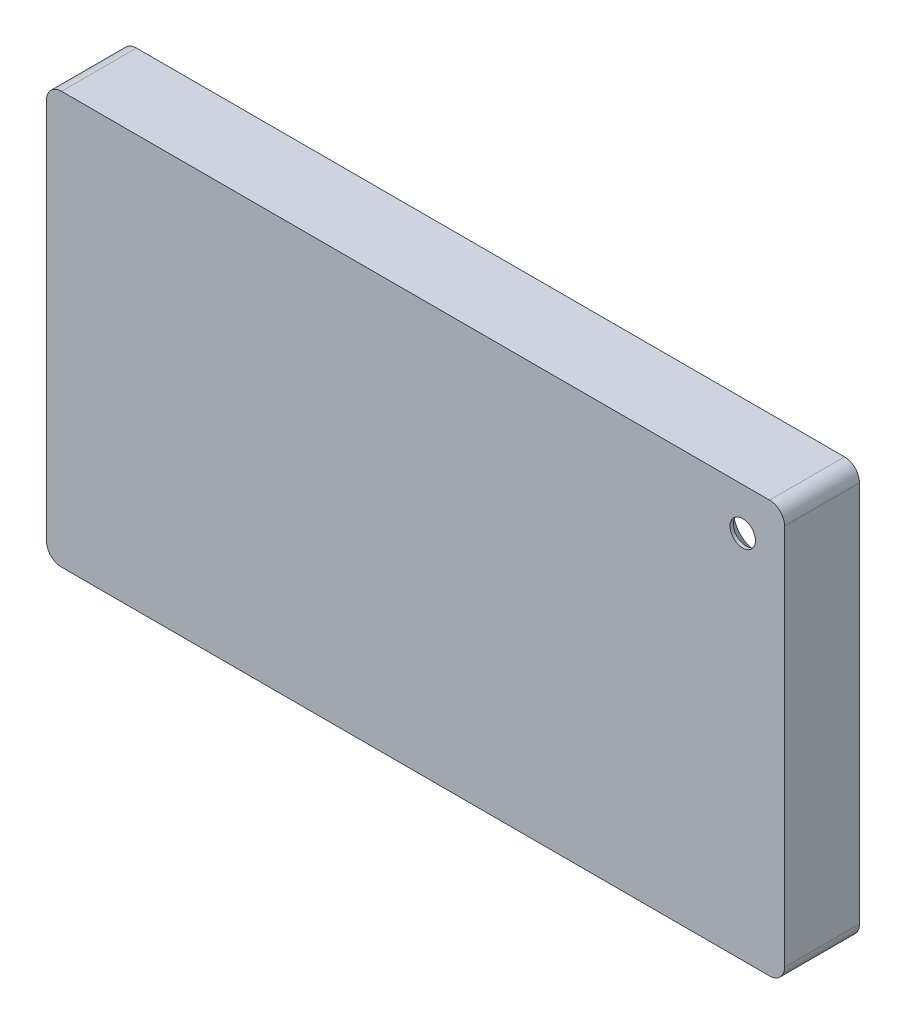
SolidWorks part; units mm, degrees
ref_plane "Front Plane" through (0, 0, 0) normal (0, 0, 1) x (1, 0, 0)
ref_plane "Top Plane" through (0, 0, 0) normal (0, 1, 0) x (1, 0, 0)
ref_plane "Right Plane" through (0, 0, 0) normal (1, 0, 0) x (0, 0, -1)
sketch "Sketch1" plane through (0, 0, 0) normal (0, 0, 1) x (1, 0, 0)
  line L1 (-47.25, -25.5) -> (47.25, -25.5)
  line L2 (-47.25, -25.5) -> (-47.25, 25.5)
  line L3 (-47.25, 25.5) -> (47.25, 25.5)
  line L4 (47.25, -25.5) -> (47.25, 25.5)
  line L5 (-47.25, -25.5) -> (47.25, 25.5) construction
  line L6 (-47.25, 25.5) -> (47.25, -25.5) construction
  point P0 (0, 0)
  dimension "D1" = 51
  dimension "D2" = 94.5
extrude "Boss-Extrude1" add sketch "Sketch1" along normal blind 2
sketch "Sketch2" plane through (0, 0, 2) normal (0, 0, 1) x (1, 0, 0)
  line L0 (-49.25, 27.5) -> (-49.25, -27.5)
  line L1 (-49.25, -27.5) -> (49.25, -27.5)
  line L2 (49.25, -27.5) -> (49.25, 27.5)
  line L3 (49.25, 27.5) -> (-49.25, 27.5)
  line L4 (47.25, -25.5) -> (47.25, 25.5)
  line L5 (47.25, 25.5) -> (-47.25, 25.5)
  line L6 (-47.25, 25.5) -> (-47.25, -25.5)
  line L7 (-47.25, -25.5) -> (47.25, -25.5)
  line L8 (47.25, -25.5) -> (47.25, 25.5)
  line L9 (47.25, 25.5) -> (-47.25, 25.5)
  line L10 (-47.25, 25.5) -> (-47.25, -25.5)
  line L11 (-47.25, -25.5) -> (47.25, -25.5)
  dimension "D1" = 0
  dimension "D2" = 2
extrude "Boss-Extrude2" add sketch "Sketch2" against normal blind 10
sketch "Sketch3" plane through (0, 0, 2) normal (0, 0, 1) x (1, 0, 0)
  circle A0 centre (43.6658, 21.8683) radius 1.7
  dimension "D1" = 3.4
extrude "Cut-Extrude1" cut sketch "Sketch3" against normal through all
chamfer "Chamfer1" distance 1.55 angle 45 1 edges at (41.9658, 21.8683, 0)
ref_plane "Plane1" through (0, 0, -18) normal (0, 0, -1) x (-1, 0, 0)
sketch "Sketch5" plane through (0, 0, -18) normal (0, 0, -1) x (-1, 0, 0)
  circle A0 centre (49.25, -27.5) radius 4
  dimension "D1" = 8
sketch "Sketch6" plane through (0, 0, -8) normal (0, 0, -1) x (-1, 0, 0)
  line L0 (47.25, -25.5) -> (-47.25, -25.5) construction
  line L1 (47.25, -25.5) -> (38.6349, -25.5)
  line L2 (47.25, 25.5) -> (47.25, -25.5) construction
  line L3 (47.25, -19.861) -> (47.25, -25.5)
  line L4 (49.25, 27.5) -> (-49.25, 27.5)
  line L5 (-49.25, 27.5) -> (-49.25, -27.5)
  line L6 (-49.25, -27.5) -> (49.25, -27.5)
  line L7 (49.25, -27.5) -> (49.25, 27.5)
  line L10 (38.6349, -27.5) -> (49.25, -27.5)
  line L11 (49.25, -27.5) -> (49.25, -19.861)
  line L12 (38.6349, -25.5) -> (38.6349, -27.5)
  line L13 (47.25, -19.861) -> (49.25, -19.861)
  dimension "D1" = 0
fillet "Fillet1" radius 2 4 edges at (49.25, 27.5, -3) (-49.25, 27.5, -3) (-49.25, -27.5, -3) (49.25, -27.5, -3)
sketch "Sketch7" plane through (0, 0, 0) normal (0, 0, -1) x (-1, 0, 0)
  text T0 "Arduino \r\n  Nano"
  text T1 "UART to USB"
  point P1 (0, 0)
  point P2 (0, 0)
  point P4 (-41.2984, 13.6391)
  point P5 (-38.0341, -10.9941)
  point P6 (-39.1472, -7.9981)
  point P7 (-37.8128, 6.8151)
  point P8 (-41.6078, 6.5349)
  point P9 (-41.5511, 9.695)
  point P10 (-41.5511, -10.5471)
extrude "Cut-Extrude2" cut sketch "Sketch7" against normal blind 1
